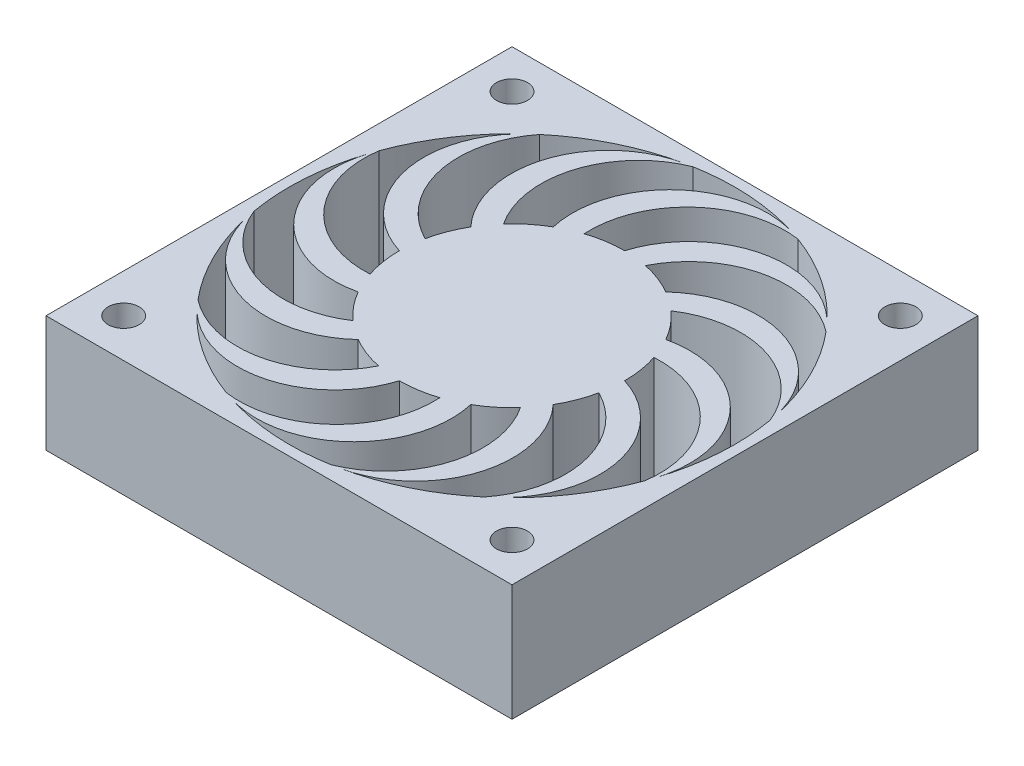
SolidWorks part; units mm, degrees
ref_plane "Front Plane" through (0, 0, 0) normal (0, 0, 1) x (1, 0, 0)
ref_plane "Top Plane" through (0, 0, 0) normal (0, 1, 0) x (1, 0, 0)
ref_plane "Right Plane" through (0, 0, 0) normal (1, 0, 0) x (0, 0, -1)
sketch "Sketch1" plane through (0, 0, 0) normal (0, 1, 0) x (1, 0, 0)
  line L1 (0, 0) -> (60, 0)
  line L2 (0, 0) -> (0, 60)
  line L3 (0, 60) -> (60, 60)
  line L4 (60, 0) -> (60, 60)
  dimension "D1" = 60
extrude "Boss-Extrude1" add sketch "Sketch1" along normal blind 15
sketch "Sketch2" plane through (0, 15, 0) normal (0, 1, 0) x (1, 0, 0)
  line L0 (0, 60) -> (60, 0) construction
  line L1 (60, 0) -> (60, 60) construction
  circle A0 centre (30, 30) radius 28.7
  circle A1 centre (30, 30) radius 14.5
  dimension "D1" = 1.3
  dimension "D2" = 29
extrude "Cut-Extrude1" cut sketch "Sketch2" against normal through all
sketch "Sketch3" plane through (0, 15, 0) normal (0, 1, 0) x (1, 0, 0)
  line L0 (60, 60) -> (0, 60) construction
  arc A0 (30, 44.5) -> (51.3462, 49.1841) centre (42.0019, 40.7863) cw
  circle A1 centre (30, 30) radius 14.5 construction
  circle A2 centre (30, 30) radius 28.7 construction
  arc A3 (33, 44.1863) -> (52.0016, 48.4288) centre (44.2314, 38.5565) cw
  arc A4 (30, 44.5) -> (33, 44.1863) centre (30, 30) cw
  circle A6 centre (30, 30) radius 28.7
  arc A7 (52.0016, 48.4288) -> (51.3462, 49.1841) centre (30, 30) ccw
  point P12 (30, 60)
  dimension "D3" = 12.5634
  dimension "D1" = 1
  dimension "D2" = 3
  dimension "D4" = 0
extrude "Boss-Extrude2" add sketch "Sketch3" against normal up to surface (15 mm away) up to face at (30, 0, -1.3)
pattern_circular "CirPattern1" count 12 over 360 about axis through (30, 0, -30) along (0, 1, 0) of "Boss-Extrude2"
sketch "Sketch4" plane through (0, 15, 0) normal (0, 1, 0) x (1, 0, 0)
  line L0 (0, 60) -> (60, 0) construction
  line L1 (60, 60) -> (0, 0) construction
  line L3 (5, 55) -> (55, 55) construction
  line L4 (5, 55) -> (5, 5) construction
  line L5 (5, 5) -> (55, 5) construction
  line L6 (55, 55) -> (55, 5) construction
  circle A0 centre (5, 55) radius 2
  circle A1 centre (55, 55) radius 2
  circle A2 centre (55, 5) radius 2
  circle A3 centre (5, 5) radius 2
  dimension "D2" = 4
  dimension "D1" = 50
extrude "Cut-Extrude2" cut sketch "Sketch4" against normal through all
